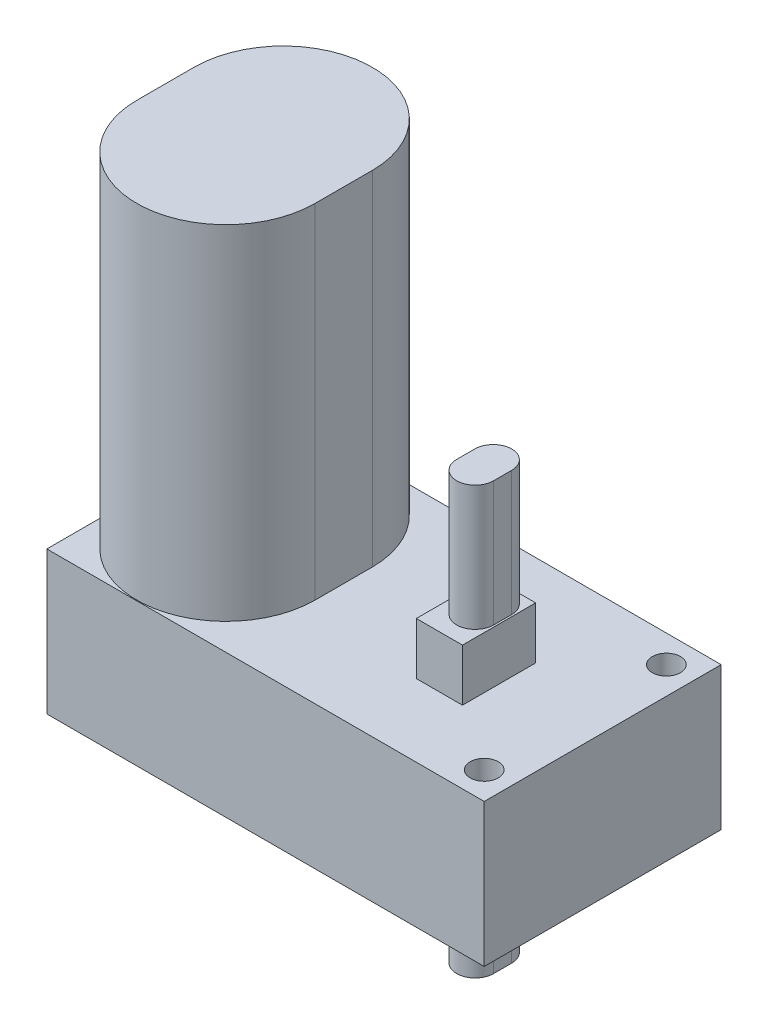
SolidWorks part; units mm, degrees
ref_plane "Front Plane" through (0, 0, 0) normal (0, 0, 1) x (1, 0, 0)
ref_plane "Top Plane" through (0, 0, 0) normal (0, 1, 0) x (1, 0, 0)
ref_plane "Right Plane" through (0, 0, 0) normal (1, 0, 0) x (0, 0, -1)
sketch "Sketch1" plane through (0, 0, 0) normal (0, 1, 0) x (1, 0, 0)
  line L1 (-21.005, -11.38) -> (21.005, -11.38)
  line L2 (-21.005, -11.38) -> (-21.005, 11.38)
  line L3 (-21.005, 11.38) -> (21.005, 11.38)
  line L4 (21.005, -11.38) -> (21.005, 11.38)
  line L5 (-21.005, -11.38) -> (21.005, 11.38) construction
  line L6 (-21.005, 11.38) -> (21.005, -11.38) construction
  point P0 (0, 0)
  dimension "D1" = 22.76
  dimension "D2" = 42.01
extrude "Boss-Extrude1" add sketch "Sketch1" along normal blind 13.73
sketch "Sketch2" plane through (0, 13.73, 0) normal (0, 1, 0) x (1, 0, 0)
  line L0 (-12.435, -2.75) -> (-12.435, 2.75) construction
  line L1 (-21.005, -2.75) -> (-21.005, 2.75)
  line L2 (-3.865, -2.75) -> (-3.865, 2.75)
  line L3 (-21.005, 11.38) -> (-21.005, -11.38) construction
  arc A0 (-21.005, -2.75) -> (-3.865, -2.75) centre (-12.435, -2.75) ccw
  arc A1 (-3.865, 2.75) -> (-21.005, 2.75) centre (-12.435, 2.75) ccw
  point P2 (-12.435, 0)
  dimension "D3" = 5.5
  dimension "D1" = 17.14
  dimension "D2" = 0
  dimension "D4" = 12.435
extrude "Boss-Extrude2" add sketch "Sketch2" along normal blind 33
sketch "Sketch3" plane through (0, 13.73, 0) normal (0, 1, 0) x (1, 0, 0)
  line L2 (10.005, -1.25) -> (10.005, 0.49) construction
  line L3 (8.23, -1.25) -> (8.23, 0.49)
  line L4 (11.78, -1.25) -> (11.78, 0.49)
  line L5 (21.005, -11.38) -> (21.005, 11.38) construction
  line L6 (-21.005, -11.38) -> (21.005, -11.38) construction
  arc A1 (8.23, -1.25) -> (11.78, -1.25) centre (10.005, -1.25) ccw
  arc A2 (11.78, 0.49) -> (8.23, 0.49) centre (10.005, 0.49) ccw
  point P8 (10.005, -0.38)
  dimension "D3" = 1.74
  dimension "D4" = 3.55
  dimension "D1" = 11
  dimension "D2" = 11
extrude "Boss-Extrude3" add sketch "Sketch3" along normal blind 17 and the other way blind 24
sketch "Sketch4" plane through (0, 13.73, 0) normal (0, 1, 0) x (1, 0, 0)
  line L1 (21.005, -11.38) -> (21.005, 11.38) construction
  line L4 (21.005, 11.38) -> (-21.005, 11.38) construction
  circle A0 centre (18.375, 8.75) radius 1.35
  circle A1 centre (18.375, -8.75) radius 1.35
  dimension "D3" = 2.7
  dimension "D4" = 2.7
  dimension "D1" = 17.5
  dimension "D2" = 2.63
  dimension "D5" = 2.63
  dimension "D6" = 2.63
extrude "Cut-Extrude1" cut sketch "Sketch4" against normal blind 17
sketch "Sketch5" plane through (0, 13.73, 0) normal (0, 1, 0) x (1, 0, 0)
  line L1 (7.5245, -4.419) -> (11.9556, -4.419)
  line L2 (7.5245, -4.419) -> (7.5245, 2.6092)
  line L3 (7.5245, 2.6092) -> (11.9556, 2.6092)
  line L4 (11.9556, -4.419) -> (11.9556, 2.6092)
  line L5 (7.5245, -4.419) -> (11.9556, 2.6092) construction
  line L6 (7.5245, 2.6092) -> (11.9556, -4.419) construction
  point P0 (9.7401, -0.9049)
  dimension "D1" = 4.4311
  dimension "D2" = 7.0282
extrude "Boss-Extrude4" add sketch "Sketch5" along normal blind 5
